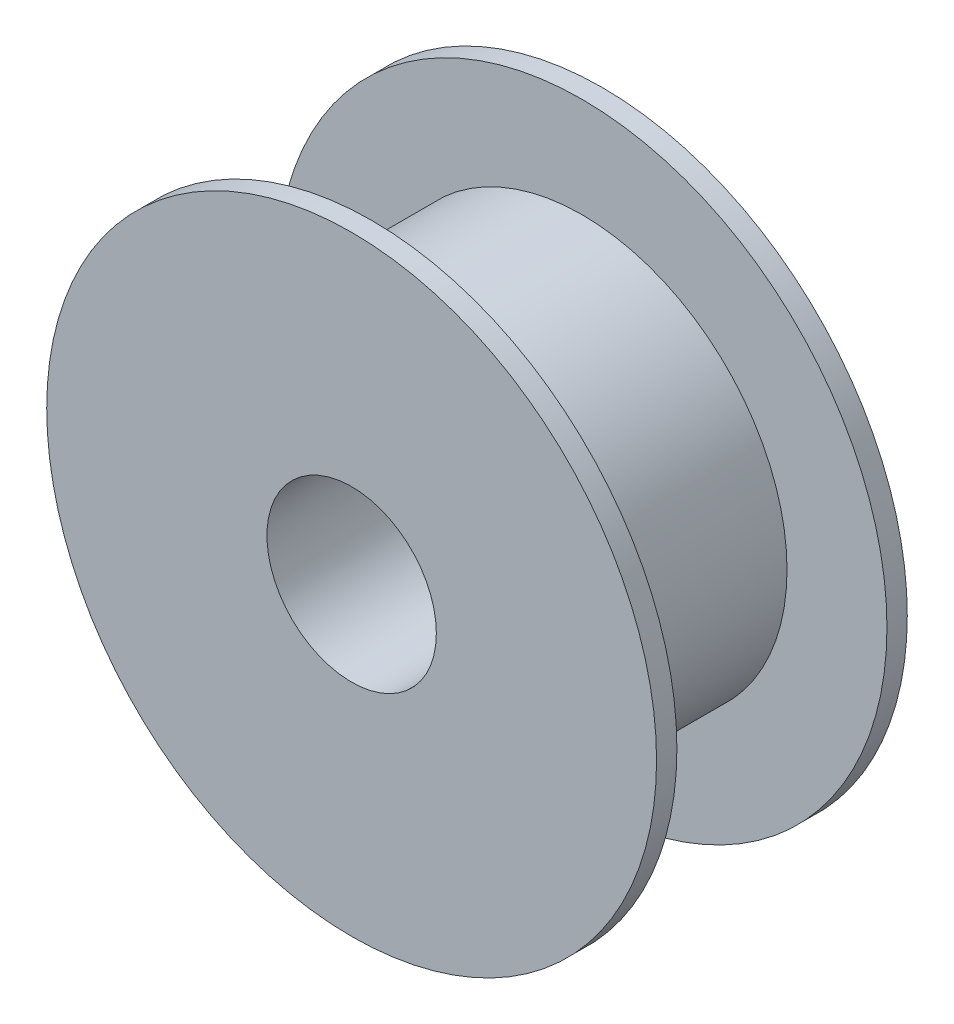
SolidWorks part; units mm, degrees
ref_plane "Спереди" through (0, 0, 0) normal (0, 0, 1) x (1, 0, 0)
ref_plane "Сверху" through (0, 0, 0) normal (0, 1, 0) x (1, 0, 0)
ref_plane "Справа" through (0, 0, 0) normal (1, 0, 0) x (0, 0, -1)
sketch "Эскиз1" plane through (0, 0, 0) normal (0, 0, 1) x (1, 0, 0)
  circle A0 centre (0, 0) radius 2.5
  circle A1 centre (0, 0) radius 6.05
  dimension "D1" = 5
  dimension "D2" = 12.1
extrude "Бобышка-Вытянуть1" add sketch "Эскиз1" along normal blind 7.4
sketch "Эскиз2" plane through (0, 0, 7.4) normal (0, 0, 1) x (1, 0, 0)
  circle A0 centre (0, 0) radius 9
  dimension "D1" = 18
extrude "Бобышка-Вытянуть2" add sketch "Эскиз2" against normal blind 0.6
sketch "Эскиз3" plane through (0, 0, 0) normal (0, 0, -1) x (-1, 0, 0)
  circle A0 centre (0, 0) radius 9
  dimension "D1" = 18
extrude "Бобышка-Вытянуть3" add sketch "Эскиз3" against normal blind 0.6
sketch "Эскиз4" plane through (0, 0, 7.4) normal (0, 0, 1) x (1, 0, 0)
  circle A0 centre (0, 0) radius 2.5
  dimension "D1" = 5
extrude "Вырез-Вытянуть1" cut sketch "Эскиз4" against normal through all
